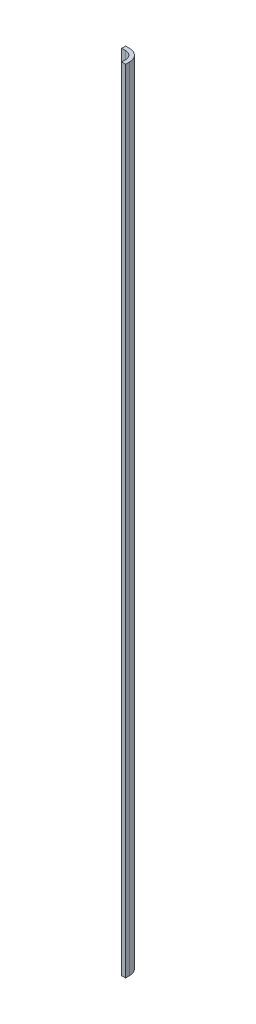
SolidWorks part; units mm, degrees
ref_plane "Front Plane" through (0, 0, 0) normal (0, 0, 1) x (1, 0, 0)
ref_plane "Top Plane" through (0, 0, 0) normal (0, 1, 0) x (1, 0, 0)
ref_plane "Right Plane" through (0, 0, 0) normal (1, 0, 0) x (0, 0, -1)
sketch "Sketch1" plane through (0, 0, 0) normal (0, 1, 0) x (1, 0, 0)
  line L5 (-43.16, 38.4159) -> (43.16, -38.4159) construction
  line L6 (-43.16, -38.4159) -> (43.16, 38.4159) construction
  line L7 (-39.16, -34.4159) -> (-38.6661, -34.4159)
  line L8 (39.16, 28.4159) -> (39.16, 26.4159)
  line L9 (-39.16, 34.4159) -> (-38.6661, 34.4159)
  line L11 (-37.16, -32.4159) -> (-36.4191, -32.4159)
  line L12 (37.16, 28.4159) -> (37.16, 26.4159)
  line L13 (-37.16, 32.4159) -> (-36.4191, 32.4159)
  line L14 (31.16, 34.4159) -> (31.16, 32.4159)
  line L15 (37.16, 26.4159) -> (39.16, 26.4159)
  line L16 (31.16, 34.4159) -> (33.16, 34.4159)
  line L17 (31.16, 32.4159) -> (33.16, 32.4159)
  line L18 (-39.16, 34.4159) -> (33.16, 34.4159) construction
  line L19 (38.6661, -34.4159) -> (39.16, -34.4159)
  line L20 (-37.16, 32.4159) -> (33.16, 32.4159) construction
  line L21 (36.4191, -32.4159) -> (37.16, -32.4159)
  line L22 (-37.16, 32.4159) -> (-37.16, -32.4159) construction
  line L23 (-39.16, 34.4159) -> (-39.16, -34.4159) construction
  line L24 (-39.16, -34.4159) -> (39.16, -34.4159) construction
  line L26 (-37.16, -32.4159) -> (37.16, -32.4159) construction
  line L27 (39.16, 28.4159) -> (39.16, -34.4159) construction
  line L28 (37.16, 28.4159) -> (37.16, -32.4159) construction
  arc A1 (33.16, 34.4159) -> (39.16, 28.4159) centre (33.16, 28.4159) cw
  arc A2 (33.16, 32.4159) -> (37.16, 28.4159) centre (33.16, 28.4159) cw
  point P0 (0, 0)
  point P6 (33.16, 38.4159)
  point P7 (43.16, 28.4159)
  point P8 (33.16, 28.4159)
  dimension "D1" = 2
  dimension "D2" = 2
  dimension "D3" = 2
extrude "Boss-Extrude1" add sketch "Sketch1" along normal blind 400 contours L12 L15 L8 A1 L16 L14 L17 A2
